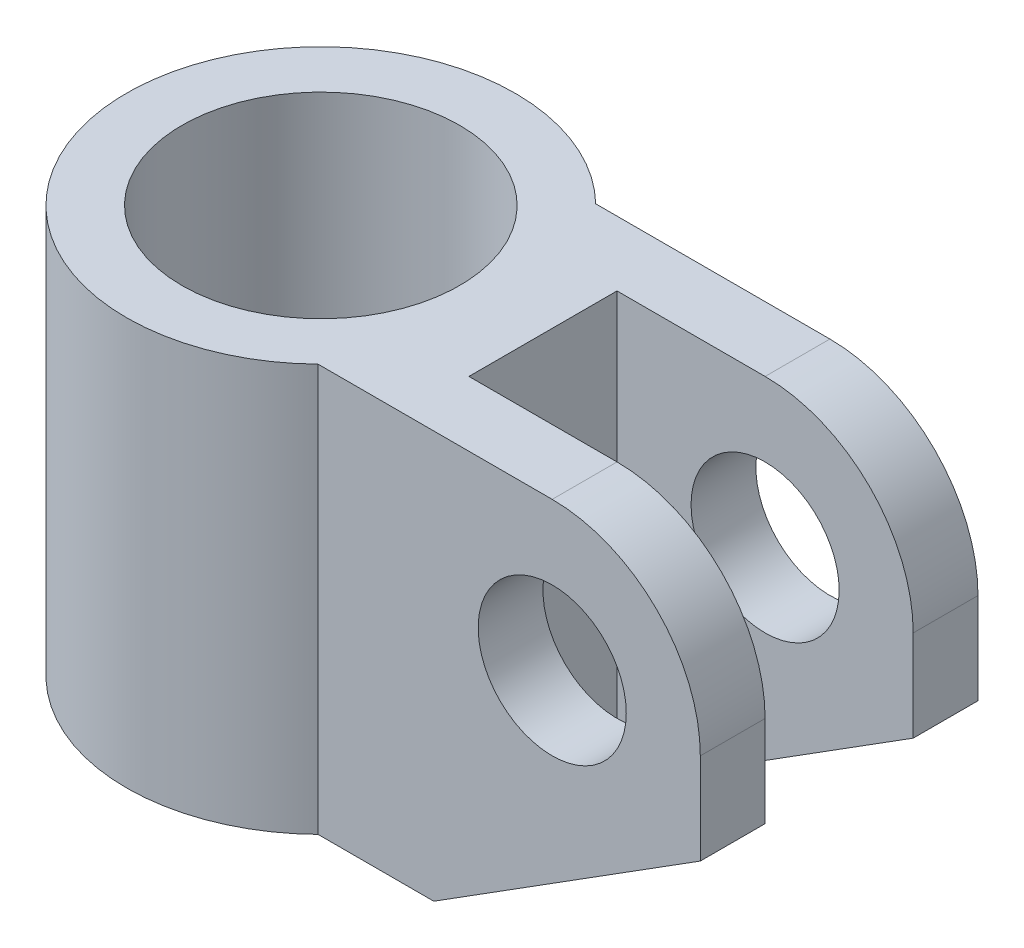
SolidWorks part; units mm, degrees
ref_plane "Front Plane" through (0, 0, 0) normal (0, 0, 1) x (1, 0, 0)
ref_plane "Top Plane" through (0, 0, 0) normal (0, 1, 0) x (1, 0, 0)
ref_plane "Right Plane" through (0, 0, 0) normal (1, 0, 0) x (0, 0, -1)
sketch "Sketch1" plane through (0, 0, 0) normal (0, 1, 0) x (1, 0, 0)
  line L0 (28, 7.5) -> (7.3485, 7.5)
  line L1 (28, 7.5) -> (28, 4)
  line L2 (28, -7.5) -> (7.3485, -7.5)
  line L3 (0, 0) -> (28, 0) construction
  line L4 (12, 0) -> (0, 0) construction
  line L5 (28, -4) -> (12, -4)
  line L7 (28, 4) -> (12, 4)
  line L8 (12, -4) -> (12, 4)
  line L9 (28, -4) -> (28, -7.5)
  line L10 (28, 7.5) -> (28, -7.5) construction
  circle A0 centre (0, 0) radius 7.5
  arc A2 (7.3485, 7.5) -> (7.3485, -7.5) centre (0, 0) ccw
  dimension "D1" = 15
  dimension "D2" = 10.5
  dimension "D3" = 15
  dimension "D4" = 28
  dimension "D5" = 8
  dimension "D6" = 12
extrude "Boss-Extrude1" add sketch "Sketch1" along normal blind 22
sketch "Sketch2" plane through (0, 0, 7.5) normal (0, 0, 1) x (1, 0, 0)
  line L0 (28, 9.0775) -> (13.602, 0)
  line L1 (28, 22) -> (28, 0) construction
  line L2 (7.3485, 0) -> (28, 0) construction
  line L3 (13.602, 0) -> (28, 0)
  line L4 (28, 0) -> (28, 9.0775)
  line L5 (28, 9.0775) -> (28, 22) construction
  line L7 (7.3485, 22) -> (28, 22) construction
  line L8 (20, 22) -> (20, 25.7645)
  line L9 (20, 25.7645) -> (29.4232, 25.7645)
  line L10 (29.4232, 25.7645) -> (29.4232, 14)
  line L11 (29.4232, 14) -> (28, 14)
  circle A0 centre (20, 14) radius 4
  arc A1 (28, 14) -> (20, 22) centre (20, 14) ccw
  dimension "D3" = 8
  dimension "D1" = 8
  dimension "D2" = 8
extrude "Cut-Extrude1" cut sketch "Sketch2" against normal up to surface (15 mm away) up to face at (17.6742, 11, -7.5)
